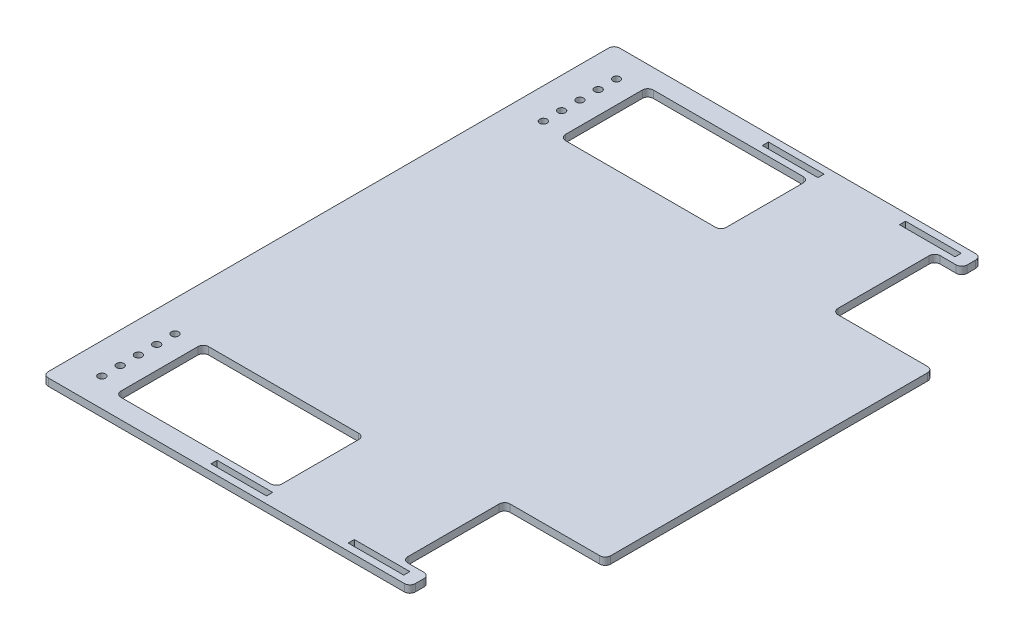
SolidWorks part; units mm, degrees
ref_plane "Front Plane" through (0, 0, 0) normal (0, 0, 1) x (1, 0, 0)
ref_plane "Top Plane" through (0, 0, 0) normal (0, 1, 0) x (1, 0, 0)
ref_plane "Right Plane" through (0, 0, 0) normal (1, 0, 0) x (0, 0, -1)
sketch "Sketch1" plane through (0, 0, 0) normal (0, 1, 0) x (1, 0, 0)
  line L0 (-112.8, 156.215) -> (-112.8, -156.215)
  line L1 (-112.8, 156.215) -> (87.95, 156.215)
  line L2 (-112.8, -156.215) -> (87.95, -156.215)
  line L3 (87.95, 156.215) -> (87.95, 145.555)
  line L4 (87.95, 145.555) -> (73.17, 145.555)
  line L5 (73.17, 145.555) -> (73.17, 89.625)
  line L6 (-215.5487, 0) -> (286.775, 0) construction
  line L7 (73.17, 89.625) -> (128.17, 89.625)
  line L8 (128.17, 89.625) -> (128.17, -89.625)
  line L9 (73.17, -89.625) -> (128.17, -89.625)
  line L10 (73.17, -145.555) -> (73.17, -89.625)
  line L11 (87.95, -145.555) -> (73.17, -145.555)
  line L12 (87.95, -156.215) -> (87.95, -145.555)
  line L13 (50.39, 152.415) -> (80.79, 152.415)
  line L14 (-83.71, 145.555) -> (4.29, 145.555)
  line L15 (-83.71, 145.555) -> (-83.71, 97.555)
  line L16 (-83.71, 97.555) -> (4.29, 97.555)
  line L17 (4.29, 145.555) -> (4.29, 97.555)
  line L18 (-24.61, 152.415) -> (5.79, 152.415)
  line L19 (-24.61, 152.415) -> (-24.61, 149.065)
  line L20 (-24.61, 149.065) -> (5.79, 149.065)
  line L21 (5.79, 152.415) -> (5.79, 149.065)
  line L22 (50.39, 152.415) -> (50.39, 149.065)
  line L23 (50.39, 149.065) -> (80.79, 149.065)
  line L24 (80.79, 152.415) -> (80.79, 149.065)
  line L25 (50.39, -152.415) -> (50.39, -149.065)
  line L26 (50.39, -149.065) -> (80.79, -149.065)
  line L27 (80.79, -152.415) -> (80.79, -149.065)
  line L28 (50.39, -152.415) -> (80.79, -152.415)
  line L29 (-24.61, -149.065) -> (5.79, -149.065)
  line L30 (5.79, -152.415) -> (5.79, -149.065)
  line L31 (-24.61, -152.415) -> (5.79, -152.415)
  line L32 (-24.61, -152.415) -> (-24.61, -149.065)
  line L33 (-83.71, -97.555) -> (4.29, -97.555)
  line L34 (4.29, -145.555) -> (4.29, -97.555)
  line L35 (-83.71, -145.555) -> (4.29, -145.555)
  line L36 (-83.71, -145.555) -> (-83.71, -97.555)
  circle A0 centre (-96, 140.715) radius 2
  circle A1 centre (-96, 130.715) radius 2
  circle A2 centre (-96, 120.715) radius 2
  circle A3 centre (-96, 110.715) radius 2
  circle A4 centre (-96, 100.715) radius 2
  circle A5 centre (-96, -100.715) radius 2
  circle A6 centre (-96, -110.715) radius 2
  circle A7 centre (-96, -120.715) radius 2
  circle A8 centre (-96, -130.715) radius 2
  circle A9 centre (-96, -140.715) radius 2
  point P13 (128.17, 0)
  dimension "D11" = 4
  dimension "D13" = 112.8
  dimension "D25" = 16.8
  dimension "D26" = 16.8
  dimension "D3" = 200.75
  dimension "D4" = 14.78
  dimension "D5" = 55.93
  dimension "D6" = 10.66
  dimension "D7" = 48
  dimension "D8" = 88
  dimension "D9" = 10.66
  dimension "D10" = 312.43
  dimension "D12" = 15.5
  dimension "D15" = 30.4
  dimension "D16" = 3.35
  dimension "D17" = 240.97
  dimension "D18" = 3.8
  dimension "D19" = 3.8
  dimension "D20" = 44.6
  dimension "D21" = 3.35
  dimension "D22" = 29.09
  dimension "D23" = 30.4
  dimension "D24" = 10
  dimension "D27" = 88.19
  dimension "D14" = 5
extrude "Boss-Extrude1" add sketch "Sketch1" along normal blind 4
fillet "Fillet1" radius 3 20 edges at (-112.8, 2, 156.215) (4.29, 2, 97.555) (4.29, 2, 145.555) (-83.71, 2, 145.555) (-83.71, 2, 97.555) (87.95, 2, 156.215) (87.95, 2, 145.555) (73.17, 2, 145.555) (73.17, 2, 89.625) (128.17, 2, 89.625) (-112.8, 2, -156.215) (4.29, 2, -97.555) (4.29, 2, -145.555) (-83.71, 2, -145.555) (-83.71, 2, -97.555) (128.17, 2, -89.625) (73.17, 2, -89.625) (73.17, 2, -145.555) (87.95, 2, -156.215) (87.95, 2, -145.555)
